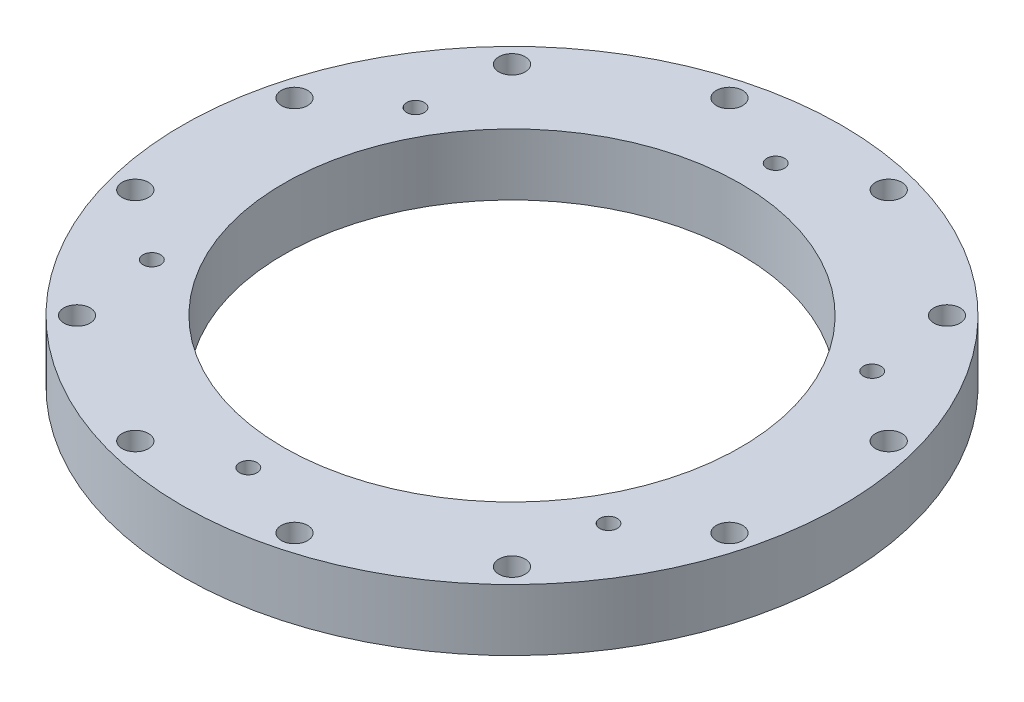
SolidWorks part; units mm, degrees
ref_plane "Front Plane" through (0, 0, 0) normal (0, 0, 1) x (1, 0, 0)
ref_plane "Top Plane" through (0, 0, 0) normal (0, 1, 0) x (1, 0, 0)
ref_plane "Right Plane" through (0, 0, 0) normal (1, 0, 0) x (0, 0, -1)
sketch "Sketch1" plane through (0, 0, 0) normal (0, 1, 0) x (1, 0, 0)
  line L0 (-53.2191, 0) -> (0, 0) construction
  line L1 (0, 0) -> (-55.1529, -14.7782) construction
  circle A0 centre (0, 0) radius 37.5
  circle A1 centre (0, 0) radius 30 construction
  circle A2 centre (0, 0) radius 26
  circle A3 centre (0, 30) radius 1
  circle A4 centre (25.9808, 15) radius 1
  circle A5 centre (25.9808, -15) radius 1
  circle A6 centre (0, -30) radius 1
  circle A7 centre (-25.9808, -15) radius 1
  circle A8 centre (-25.9808, 15) radius 1
  circle A9 centre (0, 0) radius 35 construction
  circle A10 centre (-33.8074, -9.0587) radius 1.5
  circle A11 centre (-33.8074, 9.0587) radius 1.5
  circle A12 centre (-24.7487, 24.7487) radius 1.5
  circle A13 centre (-9.0587, 33.8074) radius 1.5
  circle A14 centre (9.0587, 33.8074) radius 1.5
  circle A15 centre (24.7487, 24.7487) radius 1.5
  circle A16 centre (33.8074, 9.0587) radius 1.5
  circle A17 centre (33.8074, -9.0587) radius 1.5
  circle A18 centre (24.7487, -24.7487) radius 1.5
  circle A19 centre (9.0587, -33.8074) radius 1.5
  circle A20 centre (-9.0587, -33.8074) radius 1.5
  circle A21 centre (-24.7487, -24.7487) radius 1.5
  point P19 (0, 0)
  point P47 (0, 0)
  dimension "D1" = 75
  dimension "D2" = 52
  dimension "D3" = 60
  dimension "D4" = 2
  dimension "D7" = 70
  dimension "D8" = 3
  dimension "D6" = 15
  dimension "D5" = 6
  dimension "D9" = 12
extrude "Boss-Extrude1" add sketch "Sketch1" along normal blind 7
